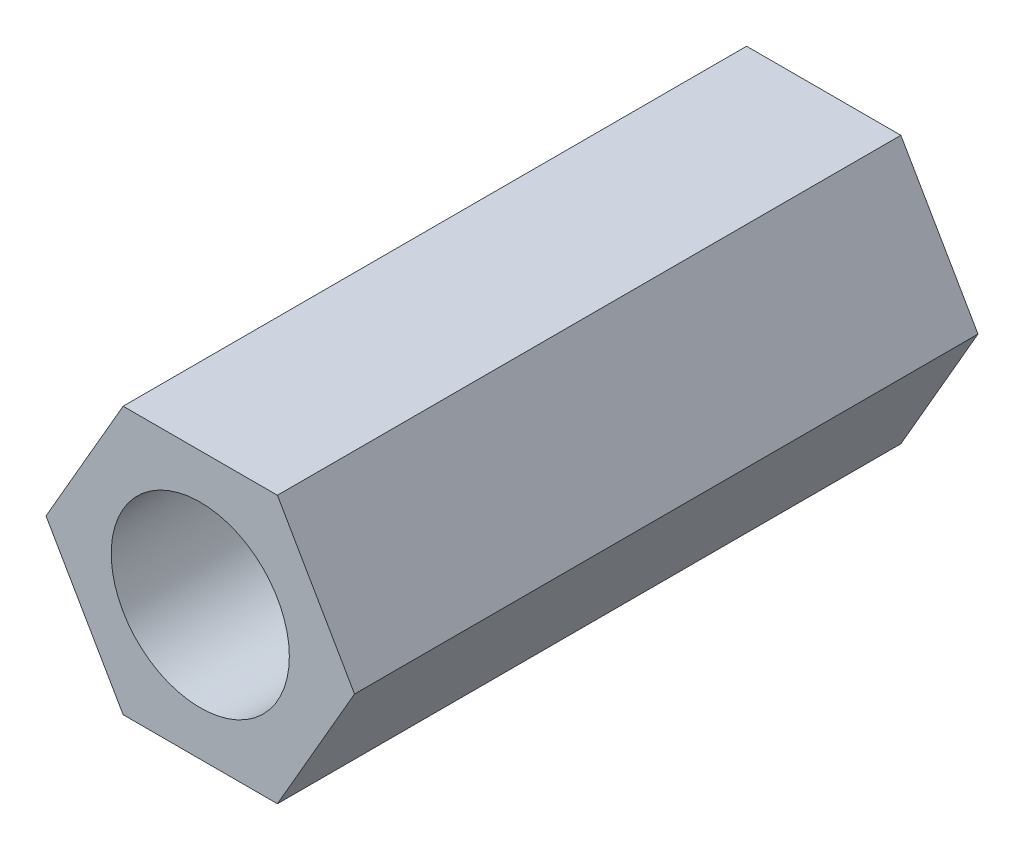
SolidWorks part; units mm, degrees
ref_plane "前视基准面" through (0, 0, 0) normal (0, 0, 1) x (1, 0, 0)
ref_plane "上视基准面" through (0, 0, 0) normal (0, 1, 0) x (1, 0, 0)
ref_plane "右视基准面" through (0, 0, 0) normal (1, 0, 0) x (0, 0, -1)
sketch "草图1" plane through (0, 0, 0) normal (0, 0, 1) x (1, 0, 0)
  line L1 (1.7321, 0) -> (0.866, 1.5)
  line L2 (0.866, 1.5) -> (-0.866, 1.5)
  line L3 (-0.866, 1.5) -> (-1.7321, 0)
  line L4 (-1.7321, 0) -> (-0.866, -1.5)
  line L5 (-0.866, -1.5) -> (0.866, -1.5)
  line L6 (0.866, -1.5) -> (1.7321, 0)
  circle A0 centre (0, 0) radius 1
  circle A1 centre (0, 0) radius 1.5 construction
  dimension "D1" = 2
  dimension "D2" = 3
extrude "凸台-拉伸1" add sketch "草图1" along normal blind 7
